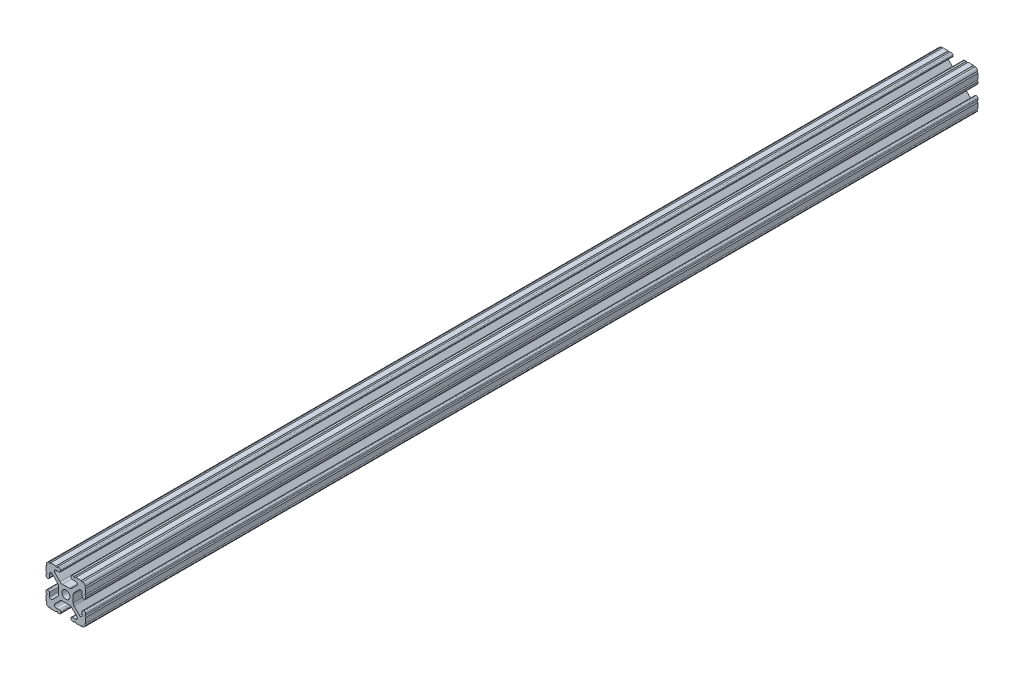
SolidWorks part; units mm, degrees
ref_plane "Front Plane" through (0, 0, 0) normal (0, 0, 1) x (1, 0, 0)
ref_plane "Top Plane" through (0, 0, 0) normal (0, 1, 0) x (1, 0, 0)
ref_plane "Right Plane" through (0, 0, 0) normal (1, 0, 0) x (0, 0, -1)
sketch "Sketch2" plane through (0, 0, 0) normal (0, 0, 1) x (1, 0, 0)
  line L0 (0, 12.7) -> (0, -12.7) construction
  line L1 (-12.7, 0) -> (12.7, 0) construction
  line L2 (3.2512, -12.7) -> (12.7, -12.7)
  line L3 (12.7, -12.7) -> (12.7, -3.2512)
  line L4 (3.2512, -12.7) -> (3.2512, -10.4902)
  line L5 (3.2512, -10.4902) -> (8.9276, -10.4902)
  line L6 (8.9276, -10.4902) -> (3.0856, -4.6482)
  line L7 (0, 0) -> (12.7, -12.7) construction
  line L8 (12.7, -3.2512) -> (10.4902, -3.2512)
  line L9 (10.4902, -3.2512) -> (10.4902, -8.9276)
  line L10 (10.4902, -8.9276) -> (4.6482, -3.0856)
  circle A0 centre (0, 0) radius 2.6035
  arc A1 (6.3485, -10.4902) -> (7.1039, -8.6665) centre (6.3485, -9.4219) ccw construction
  point P8 (0, -4.6482)
  dimension "Center Hole Diameter" = 5.207
  dimension "Rail Height" = 25.4
  dimension "Rail Width" = 25.4
  dimension "T-Slot Width" = 6.5024
  dimension "Slot Inner Width" = 14.8336
  dimension "Thickness" = 2.2098
  dimension "Slot Depth" = 5.842
  dimension "D1" = 2.2098
sketch "Sketch3" plane through (0, 0, 0) normal (1, 0, 0) x (0, 0, -1)
  line L0 (-1524, -12.7) -> (1524, -12.7) construction
  line L1 (-1498.6, 0) -> (1498.6, 0) construction
  dimension "Length" = 3048
  dimension "D1" = 25.4
sketch "Sketch4" plane through (0, 0, 0) normal (0, 0, 1) x (1, 0, 0)
  line L0 (4.1904, -12.7) -> (10.1173, -12.7)
  line L1 (3.2512, -12.7) -> (12.7, -12.7) construction
  line L2 (3.2512, -12.7) -> (3.2512, -10.4902) construction
  line L3 (3.2512, -10.4902) -> (8.9276, -10.4902) construction
  line L4 (3.2512, -11.4294) -> (3.2512, -11.7608)
  line L5 (4.1904, -10.4902) -> (6.3485, -10.4902)
  line L6 (0, -4.6482) -> (2.164, -4.6482)
  line L7 (8.9276, -10.4902) -> (3.0856, -4.6482) construction
  line L8 (3.7373, -5.2999) -> (7.1039, -8.6665)
  line L9 (12.7, -12.7) -> (12.7, -3.2512) construction
  line L10 (10.4902, -8.9276) -> (4.6482, -3.0856) construction
  line L11 (10.4902, -3.2512) -> (10.4902, -8.9276) construction
  line L12 (10.4902, -6.3485) -> (10.4902, -4.1904)
  line L13 (12.7, -3.2512) -> (10.4902, -3.2512) construction
  line L14 (11.4294, -3.2512) -> (11.7608, -3.2512)
  line L15 (12.7, -4.1904) -> (12.7, -10.1173)
  line L16 (8.6665, -7.1039) -> (5.2999, -3.7373)
  line L17 (4.6482, 0) -> (4.6482, -2.164)
  line L18 (-12.7, 0) -> (12.7, 0) construction
  line L19 (0, -4.6482) -> (0, -2.6035)
  line L20 (0, 12.7) -> (0, -12.7) construction
  line L21 (4.6482, 0) -> (2.6035, 0)
  arc A0 (3.2512, -11.7608) -> (4.1904, -12.7) centre (4.1904, -11.7608) ccw
  arc A2 (3.2512, -11.4294) -> (4.1904, -10.4902) centre (4.1904, -11.4294) cw
  arc A3 (6.3485, -10.4902) -> (7.1039, -8.6665) centre (6.3485, -9.4219) ccw
  arc A4 (2.164, -4.6482) -> (3.7373, -5.2999) centre (2.164, -6.8732) cw
  arc A5 (10.1173, -12.7) -> (12.7, -10.1173) centre (10.1173, -10.1173) ccw
  arc A6 (8.6665, -7.1039) -> (10.4902, -6.3485) centre (9.4219, -6.3485) ccw
  arc A7 (10.4902, -4.1904) -> (11.4294, -3.2512) centre (11.4294, -4.1904) cw
  arc A8 (11.7608, -3.2512) -> (12.7, -4.1904) centre (11.7608, -4.1904) cw
  arc A9 (5.2999, -3.7373) -> (4.6482, -2.164) centre (6.8732, -2.164) cw
  circle A10 centre (0, 0) radius 2.6035 construction
  arc A11 (0, -2.6035) -> (2.6035, 0) centre (0, 0) ccw
  dimension "D1" = 2.5827
  dimension "D2" = 2.225
  dimension "D3" = 0.9392
extrude "Boss-Extrude1" add sketch "Sketch4" along normal mid plane 3048
sketch "Sketch5" plane through (0, 0, 0) normal (0, 0, 1) x (1, 0, 0)
  line L0 (3.2512, -12.7) -> (12.7, -12.7) construction
  line L1 (4.1904, -10.4902) -> (6.3485, -10.4902) construction
  line L3 (0, 0) -> (12.7, -12.7) construction
  line L4 (6.3485, -10.4902) -> (6.3485, -12.7) construction
  line L5 (8.9276, -10.4902) -> (3.0856, -4.6482) construction
  circle A0 centre (10.3562, -12.7) radius 0.5524
  circle A1 centre (5.796, -12.7) radius 0.5524
  circle A2 centre (12.7, -10.3562) radius 0.5524
  circle A3 centre (12.7, -5.796) radius 0.5524
  point P10 (5.2694, -10.4902)
  point P12 (9.4219, -6.3485)
  dimension "D1" = 1.1049
extrude "Cut-Extrude1" cut sketch "Sketch5" against normal through all both and the other way through all
mirror "Mirror1" about plane through (0, 0, 0) normal (1, 0, 0) of bodies 137 134
mirror "Mirror2" about plane through (0, 0, 0) normal (0, 1, 0) of bodies 135
sketch "Sketch8" plane through (0, 0, 0) normal (0, 1, 0) x (1, 0, 0)
  line L0 (-12.58, 1524) -> (-12.58, -1524) construction
  line L1 (-25.28, 1536.7) -> (25.28, 1536.7)
  line L2 (-25.28, 1536.7) -> (-25.28, -952.5)
  line L3 (-25.28, -952.5) -> (25.28, -952.5)
  line L4 (25.28, 1536.7) -> (25.28, -952.5)
  line L5 (12.58, 1524) -> (12.58, -1524) construction
  line L7 (-6.3485, -1524) -> (-9.8037, -1524) construction
  dimension "D1" = 12.7
  dimension "D2" = 12.7
  dimension "D3" = 12.7
  dimension "D4" = 571.5
extrude "Cut-Extrude2" cut sketch "Sketch8" against normal through all both and the other way through all
equation "\"D1@Boss-Extrude1\"=\"Length@Sketch3\""
equation "\"D1@Sketch2\"=\"Thickness@Sketch2\""
equation "\"D2@Sketch4\"=\"Slot Inner Width@Sketch2\"*0.15"
equation "\"D1@Sketch4\"=\"D3@Sketch4\"*2.75"
equation "\"D3@Sketch4\"=\"Thickness@Sketch2\"*0.425"
equation "\"D1@Sketch5\"=\"Thickness@Sketch2\"*0.5"
